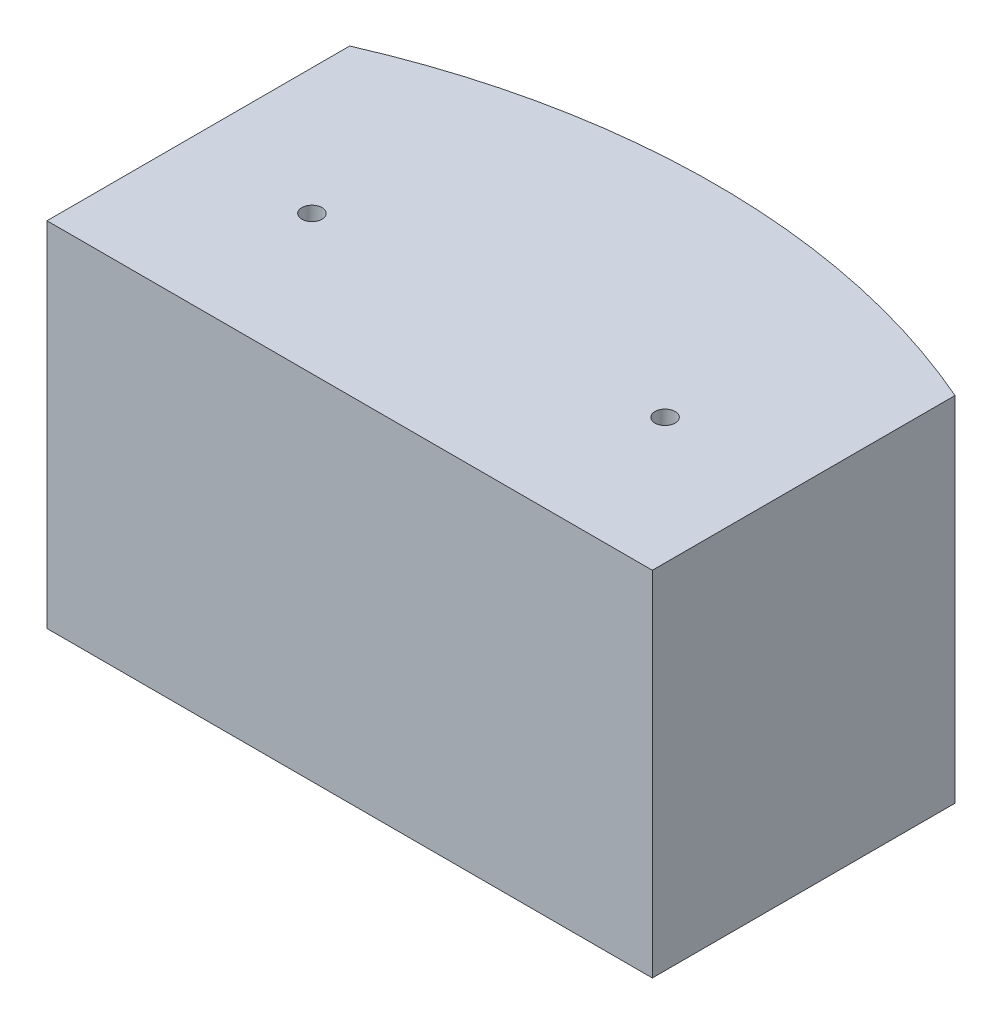
SolidWorks part; units mm, degrees
ref_plane "Front Plane" through (0, 0, 0) normal (0, 0, 1) x (1, 0, 0)
ref_plane "Top Plane" through (0, 0, 0) normal (0, 1, 0) x (1, 0, 0)
ref_plane "Right Plane" through (0, 0, 0) normal (1, 0, 0) x (0, 0, -1)
sketch "Sketch1" plane through (0, 0, 0) normal (0, 1, 0) x (1, 0, 0)
  line L0 (0, 0) -> (0, 150) construction
  line L2 (-60, 137.4773) -> (-60, 77.4773)
  line L3 (-60, 77.4773) -> (60, 77.4773)
  line L4 (60, 137.4773) -> (60, 77.4773)
  line L5 (-60, 105) -> (60, 105) construction
  arc A0 (60, 137.4773) -> (-60, 137.4773) centre (0, 0) ccw
  dimension "D1" = 300
  dimension "D2" = 120
  dimension "D3" = 45
  dimension "D4" = 60
extrude "Boss-Extrude1" add sketch "Sketch1" along normal blind 70
sketch "Sketch7" plane through (0, 0, -77.4773) normal (0, 0, 1) x (1, 0, 0)
  line L8 (-57, 3) -> (57, 3)
  line L9 (57, 3) -> (57, 67)
  line L10 (57, 67) -> (-57, 67)
  line L11 (-57, 67) -> (-57, 3)
  line L12 (-57, 3) -> (57, 3)
  line L13 (57, 3) -> (57, 67)
  line L14 (57, 67) -> (-57, 67)
  line L15 (-57, 67) -> (-57, 3)
  dimension "D1" = 3
extrude "Cut-Extrude2" cut sketch "Sketch7" against normal blind 77
sketch "Sketch8" plane through (-57, 0, 0) normal (1, 0, 0) x (0, 0, -1)
  line L0 (138.748, 67) -> (77.4773, 67) construction
  line L1 (77.4773, 3) -> (80.4773, 3)
  line L2 (77.4773, 3) -> (77.4773, 67)
  line L3 (77.4773, 67) -> (80.4773, 67)
  line L4 (80.4773, 3) -> (80.4773, 67)
  dimension "D1" = 3
extrude "Boss-Extrude3" add sketch "Sketch8" along normal up to surface (114 mm away) up to face at (57, 35, -108.1126)
sketch "Sketch9" plane through (0, 0, -80.4773) normal (0, 0, -1) x (-1, 0, 0)
  line L0 (-57, 35) -> (57, 35) construction
  line L1 (-57, 3) -> (-57, 67) construction
  line L2 (57, 3) -> (57, 67) construction
  line L3 (-57, 36.5) -> (57, 36.5)
  line L4 (-57, 33.5) -> (57, 33.5)
  line L5 (57, 67) -> (57, 3) construction
  line L6 (-57, 33.5) -> (-57, 36.5)
  line L7 (57, 36.5) -> (57, 33.5)
  dimension "D1" = 1.5
extrude "Boss-Extrude4" add sketch "Sketch9" along normal up to surface (58.2707 mm away)
sketch "Sketch10" plane through (0, 70, 0) normal (0, 1, 0) x (1, 0, 0)
  line L0 (-60, 104.9973) -> (60, 104.9973) construction
  line L1 (-60, 137.4773) -> (-60, 77.4773) construction
  line L2 (60, 77.4773) -> (60, 137.4773) construction
  line L3 (-60, 77.4773) -> (60, 77.4773) construction
  line L4 (0, 77.4773) -> (0, 104.9973) construction
  circle A0 centre (-35, 104.9973) radius 2
  circle A1 centre (35, 104.9973) radius 2
  dimension "D2" = 4
  dimension "D3" = 4
  dimension "D1" = 27.52
  dimension "D4" = 35
extrude "Cut-Extrude3" cut sketch "Sketch10" against normal up to surface (3 mm away) up to face at (0, 67, -112.4256)
